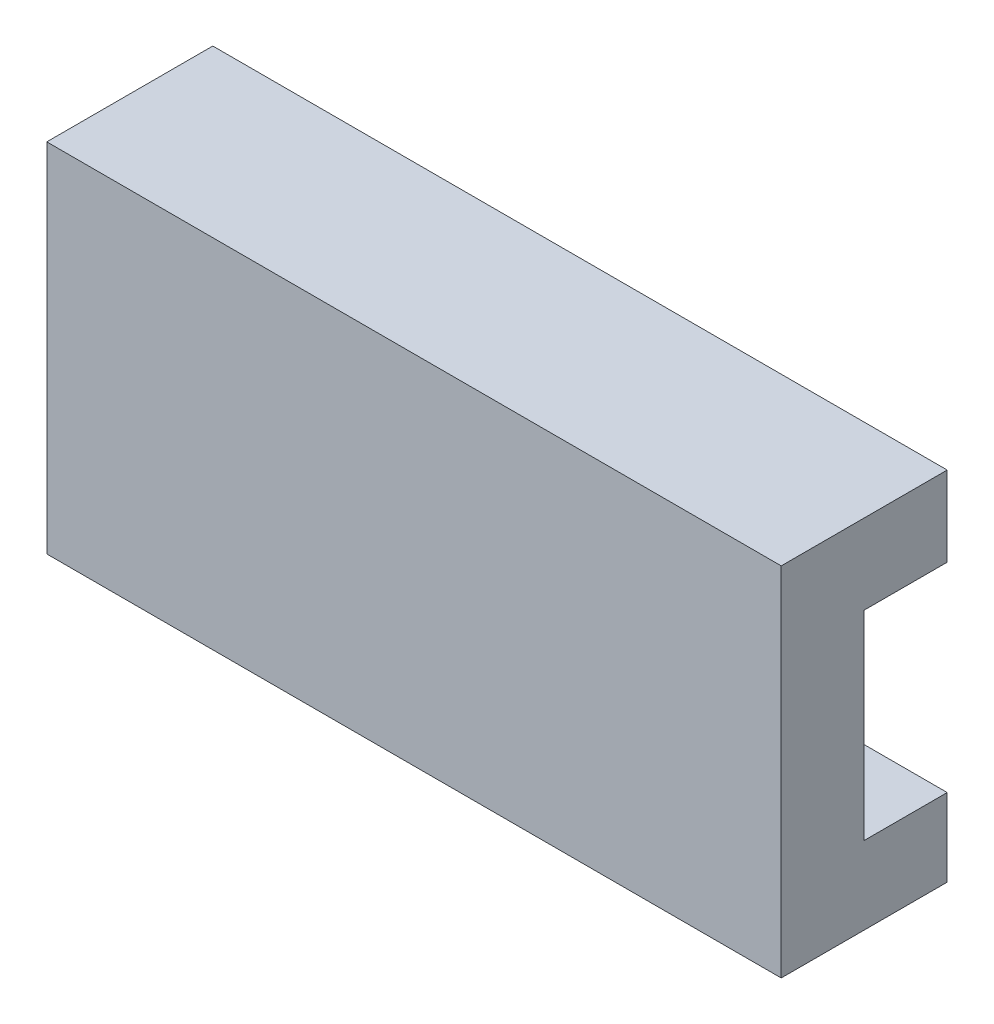
SolidWorks part; units mm, degrees
ref_plane "Front Plane" through (0, 0, 0) normal (0, 0, 1) x (1, 0, 0)
ref_plane "Top Plane" through (0, 0, 0) normal (0, 1, 0) x (1, 0, 0)
ref_plane "Right Plane" through (0, 0, 0) normal (1, 0, 0) x (0, 0, -1)
sketch "Sketch1" plane through (0, 0, 0) normal (0, 0, 1) x (1, 0, 0)
  line L0 (19.3, 7.75) -> (-19.3, 7.75) construction
  line L1 (-22.1208, 12.75) -> (22.1208, 12.75)
  line L2 (-22.1208, 12.75) -> (-22.1208, -8.75)
  line L3 (-22.1208, -8.75) -> (22.1208, -8.75)
  line L4 (22.1208, 12.75) -> (22.1208, -8.75)
  line L5 (-22.1208, 12.75) -> (22.1208, -8.75) construction
  line L6 (-22.1208, -8.75) -> (22.1208, 12.75) construction
  line L7 (-4.5, -3.75) -> (4.5, -3.75) construction
  point P0 (0, 2)
  dimension "D1" = 5
  dimension "D2" = 5
extrude "Boss-Extrude1" add sketch "Sketch1" along normal blind 10
sketch "Sketch2" plane through (0, 0, 0) normal (0, 0, 1) x (1, 0, 0)
  line L0 (22.1208, -8.75) -> (22.1208, 12.75) construction
  line L1 (-22.1208, -4.0745) -> (22.1208, -4.0745)
  line L2 (-22.1208, -4.0745) -> (-22.1208, 7.9415)
  line L3 (-22.1208, 7.9415) -> (22.1208, 7.9415)
  line L4 (22.1208, -4.0745) -> (22.1208, 7.9415)
  line L5 (-22.1208, -4.0745) -> (22.1208, 7.9415) construction
  line L6 (-22.1208, 7.9415) -> (22.1208, -4.0745) construction
  point P0 (0, 1.9335)
extrude "Cut-Extrude1" cut sketch "Sketch2" along normal blind 5
